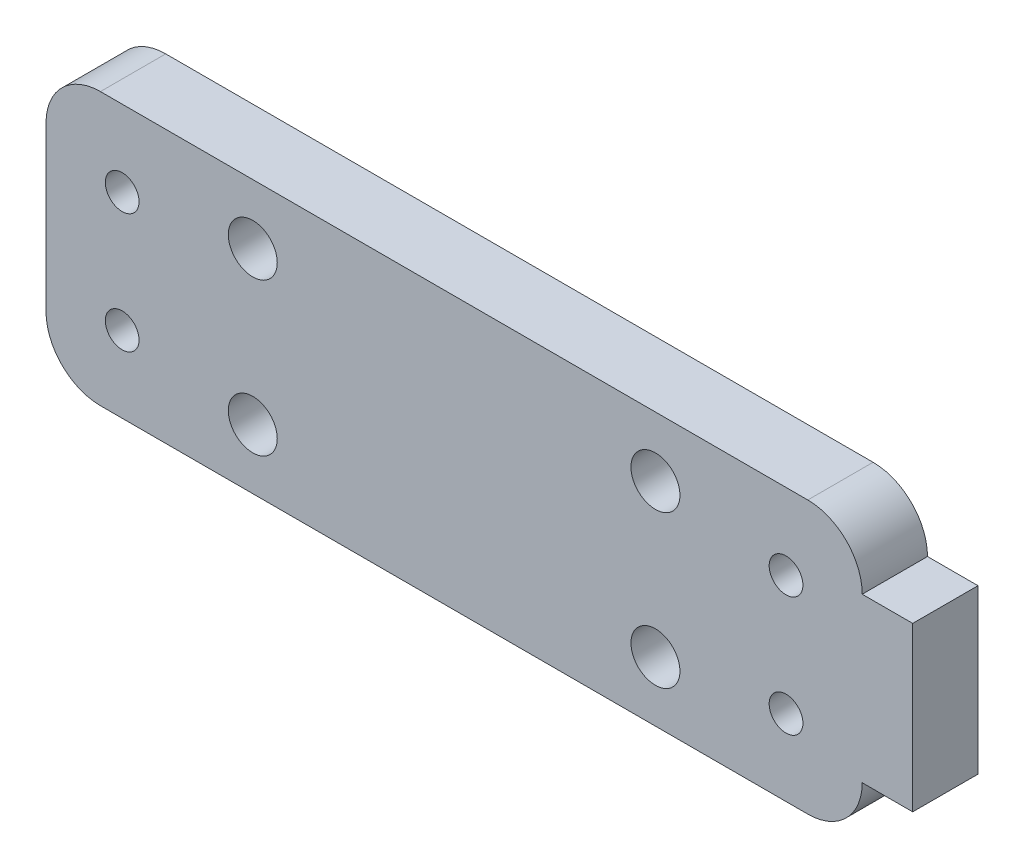
SolidWorks part; units mm, degrees
ref_plane "Front Plane" through (0, 0, 0) normal (0, 0, 1) x (1, 0, 0)
ref_plane "Top Plane" through (0, 0, 0) normal (0, 1, 0) x (1, 0, 0)
ref_plane "Right Plane" through (0, 0, 0) normal (1, 0, 0) x (0, 0, -1)
sketch "Sketch1" plane through (0, 0, 0) normal (0, 0, 1) x (1, 0, 0)
  line L1 (5, 0) -> (70, 0)
  line L2 (0, -5) -> (0, -20)
  line L3 (5, -25) -> (70, -25)
  line L4 (75, -5) -> (75, -20)
  circle A0 centre (7, -7) radius 1.55
  circle A1 centre (7, -18) radius 1.55
  circle A2 centre (68, -7) radius 1.55
  circle A3 centre (68, -18) radius 1.55
  circle A4 centre (19, -5.5) radius 2.25
  circle A5 centre (19, -19.5) radius 2.25
  circle A6 centre (56, -5.5) radius 2.25
  circle A7 centre (56, -19.5) radius 2.25
  arc A8 (70, -25) -> (75, -20) centre (70, -20) ccw
  arc A9 (75, -5) -> (70, 0) centre (70, -5) ccw
  arc A10 (5, -25) -> (0, -20) centre (5, -20) cw
  arc A11 (5, 0) -> (0, -5) centre (5, -5) ccw
  point P23 (75, -25)
  point P28 (0, -25)
  point P31 (0, 0)
  dimension "D3" = 3.1
  dimension "D4" = 3.1
  dimension "D5" = 3.1
  dimension "D6" = 3.1
  dimension "D15" = 4.5
  dimension "D16" = 4.5
  dimension "D17" = 4.5
  dimension "D18" = 4.5
  dimension "D27" = 5
  dimension "D1" = 25
  dimension "D2" = 75
  dimension "D7" = 7
  dimension "D8" = 7
  dimension "D9" = 7
  dimension "D10" = 7
  dimension "D11" = 7
  dimension "D12" = 7
  dimension "D13" = 7
  dimension "D14" = 7
  dimension "D19" = 5.5
  dimension "D20" = 5.5
  dimension "D21" = 5.5
  dimension "D22" = 5.5
  dimension "D23" = 19
  dimension "D24" = 19
  dimension "D25" = 19
  dimension "D26" = 19
extrude "Boss-Extrude1" add sketch "Sketch1" along normal blind 6
sketch "Sketch4" plane through (75, 0, 0) normal (1, 0, 0) x (0, 0, -1)
  line L1 (-6, -5) -> (0, -5)
  line L2 (-6, -5) -> (-6, -20)
  line L3 (-6, -20) -> (0, -20)
  line L4 (0, -5) -> (0, -20)
extrude "Boss-Extrude3" add sketch "Sketch4" along normal blind 4.64
